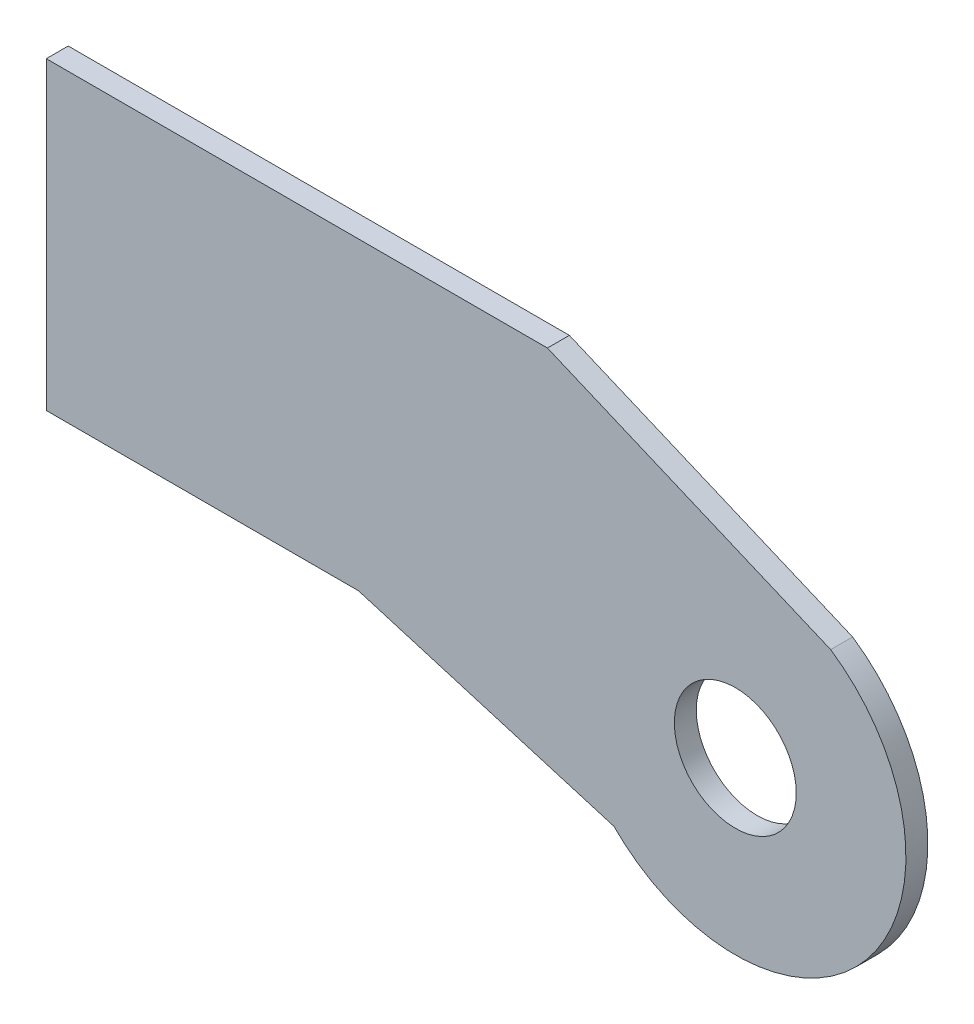
SolidWorks part; units mm, degrees
ref_plane "Plano frontal" through (0, 0, 0) normal (0, 0, 1) x (1, 0, 0)
ref_plane "Plano superior" through (0, 0, 0) normal (0, 1, 0) x (1, 0, 0)
ref_plane "Plano direito" through (0, 0, 0) normal (1, 0, 0) x (0, 0, -1)
sketch "Esboço1" plane through (0, 0, 0) normal (0, 0, 1) x (1, 0, 0)
  line L1 (-15.7803, 15.4053) -> (25.3372, 15.4053)
  line L2 (-15.7803, 15.4053) -> (-15.7803, -9.5947)
  line L3 (-15.7803, -9.5947) -> (9.8282, -9.5947)
  line L5 (-15.7803, 15.4053) -> (9.8282, -9.5947) construction
  line L6 (-15.7803, -9.5947) -> (25.3372, 15.4053) construction
  line L8 (9.8282, -9.5947) -> (30.7909, -15.8524)
  line L9 (25.3372, 15.4053) -> (48.5752, 5.5958)
  arc A1 (48.5752, 5.5958) -> (30.7909, -15.8524) centre (40.7509, -6.0137) cw
  point P0 (0, 0)
  dimension "D1" = 14
  dimension "D2" = 25
extrude "Ressalto-extrusão3" add sketch "Esboço1" along normal blind 1.8
sketch "Esboço7" plane through (0, 0, 1.8) normal (0, 0, 1) x (1, 0, 0)
  circle A0 centre (40.7509, -6.0137) radius 5
  dimension "D1" = 10
extrude "Corte-extrusão5" cut sketch "Esboço7" against normal blind 3
